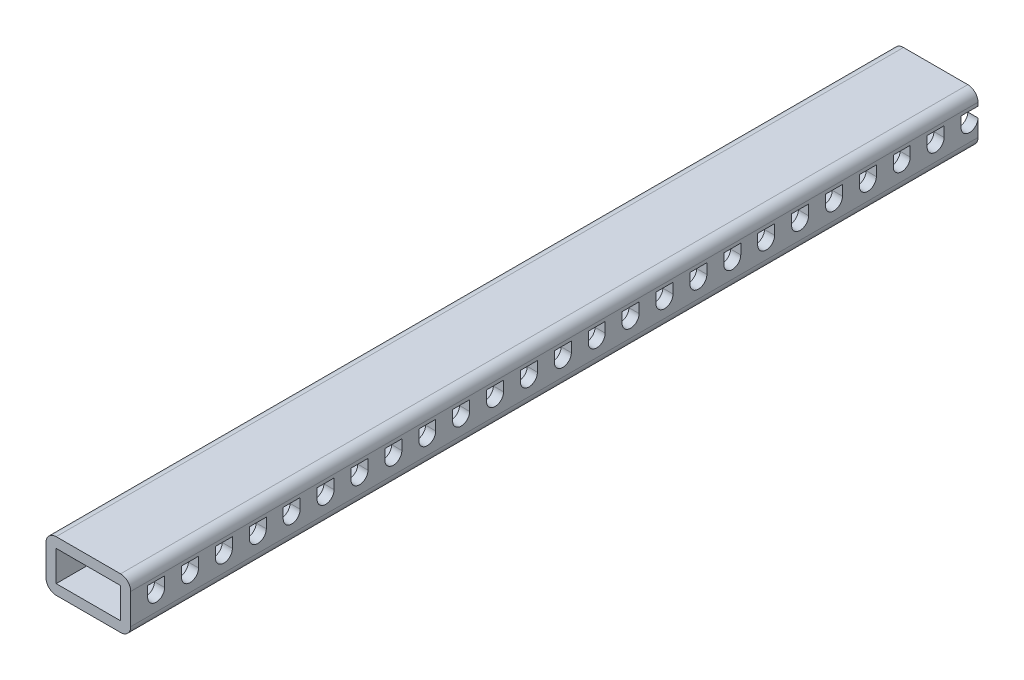
SolidWorks part; units mm, degrees
ref_plane "Front Plane" through (0, 0, 0) normal (0, 0, 1) x (1, 0, 0)
ref_plane "Top Plane" through (0, 0, 0) normal (0, 1, 0) x (1, 0, 0)
ref_plane "Right Plane" through (0, 0, 0) normal (1, 0, 0) x (0, 0, -1)
sketch "Sketch1" plane through (0, 0, 0) normal (0, 0, 1) x (1, 0, 0)
  line L1 (-12.5, 7.5) -> (12.5, 7.5)
  line L2 (-12.5, 7.5) -> (-12.5, -7.5)
  line L3 (-12.5, -7.5) -> (12.5, -7.5)
  line L4 (12.5, 7.5) -> (12.5, -7.5)
  line L5 (-12.5, 7.5) -> (12.5, -7.5) construction
  line L6 (-12.5, -7.5) -> (12.5, 7.5) construction
  point P0 (0, 0)
  dimension "D1" = 25
  dimension "D2" = 15
extrude "Boss-Extrude1" add sketch "Sketch1" along normal blind 520
sketch "Sketch2" plane through (0, 0, 520) normal (0, 0, 1) x (1, 0, 0)
  line L0 (-12.5, 7.5) -> (-12.5, -7.5) construction
  line L1 (-9.5, -4.5) -> (9.5, -4.5)
  line L2 (-9.5, -4.5) -> (-9.5, 4.5)
  line L3 (-9.5, 4.5) -> (9.5, 4.5)
  line L4 (9.5, -4.5) -> (9.5, 4.5)
  line L5 (-9.5, -4.5) -> (9.5, 4.5) construction
  line L6 (-9.5, 4.5) -> (9.5, -4.5) construction
  line L7 (12.5, 7.5) -> (-12.5, 7.5) construction
  point P0 (0, 0)
  dimension "D1" = 3
  dimension "D2" = 3
extrude "Cut-Extrude1" cut sketch "Sketch2" against normal blind 263
sketch "Sketch3" plane through (12.5, 0, 0) normal (1, 0, 0) x (0, 0, -1)
  line L1 (-520, 7.5) -> (0, 7.5) construction
  line L2 (-515, 3.5) -> (-510, 3.5)
  line L3 (-515, 3.5) -> (-515, 0.5)
  line L5 (-510, 3.5) -> (-510, 0.5)
  line L6 (-520, -7.5) -> (-520, 7.5) construction
  line L7 (-507.5, 7.5) -> (-507.5, 3.8883) construction
  line L8 (-505, 3.5) -> (-505, 0.5)
  line L9 (-500, 3.5) -> (-500, 0.5)
  line L10 (-500, 3.5) -> (-505, 3.5)
  line L11 (-497.5, 7.5) -> (-497.5, 3.8883) construction
  line L12 (-487.5, 7.5) -> (-487.5, 3.8883) construction
  line L13 (-495, 3.5) -> (-490, 3.5)
  line L14 (-495, 3.5) -> (-495, 0.5)
  line L15 (-490, 3.5) -> (-490, 0.5)
  line L16 (-485, 3.5) -> (-485, 0.5)
  line L17 (-480, 3.5) -> (-480, 0.5)
  line L18 (-480, 3.5) -> (-485, 3.5)
  line L19 (-477.5, 7.5) -> (-477.5, 3.8883) construction
  line L20 (-467.5, 7.5) -> (-467.5, 3.8883) construction
  line L21 (-485, 3.5) -> (-485, 0.5)
  line L22 (-480, 3.5) -> (-480, 0.5)
  line L23 (-480, 3.5) -> (-485, 3.5)
  line L24 (-475, 3.5) -> (-470, 3.5)
  line L25 (-475, 3.5) -> (-475, 0.5)
  line L26 (-470, 3.5) -> (-470, 0.5)
  line L27 (-465, 3.5) -> (-465, 0.5)
  line L28 (-460, 3.5) -> (-460, 0.5)
  line L29 (-460, 3.5) -> (-465, 3.5)
  line L30 (-457.5, 7.5) -> (-457.5, 3.8883) construction
  line L31 (-447.5, 7.5) -> (-447.5, 3.8883) construction
  line L32 (-437.5, 7.5) -> (-437.5, 3.8883) construction
  line L33 (-427.5, 7.5) -> (-427.5, 3.8883) construction
  line L34 (-465, 3.5) -> (-465, 0.5)
  line L35 (-460, 3.5) -> (-460, 0.5)
  line L36 (-460, 3.5) -> (-465, 3.5)
  line L37 (-455, 3.5) -> (-450, 3.5)
  line L38 (-455, 3.5) -> (-455, 0.5)
  line L39 (-450, 3.5) -> (-450, 0.5)
  line L40 (-455, 3.5) -> (-450, 3.5)
  line L41 (-455, 3.5) -> (-455, 0.5)
  line L42 (-450, 3.5) -> (-450, 0.5)
  line L43 (-445, 3.5) -> (-445, 0.5)
  line L44 (-440, 3.5) -> (-440, 0.5)
  line L45 (-440, 3.5) -> (-445, 3.5)
  line L46 (-435, 3.5) -> (-430, 3.5)
  line L47 (-435, 3.5) -> (-435, 0.5)
  line L48 (-430, 3.5) -> (-430, 0.5)
  line L49 (-425, 3.5) -> (-425, 0.5)
  line L50 (-420, 3.5) -> (-420, 0.5)
  line L51 (-420, 3.5) -> (-425, 3.5)
  line L52 (-417.5, 7.5) -> (-417.5, 3.8883) construction
  line L53 (-407.5, 7.5) -> (-407.5, 3.8883) construction
  line L54 (-397.5, 7.5) -> (-397.5, 3.8883) construction
  line L55 (-387.5, 7.5) -> (-387.5, 3.8883) construction
  line L56 (-377.5, 7.5) -> (-377.5, 3.8883) construction
  line L57 (-367.5, 7.5) -> (-367.5, 3.8883) construction
  line L58 (-357.5, 7.5) -> (-357.5, 3.8883) construction
  line L59 (-347.5, 7.5) -> (-347.5, 3.8883) construction
  line L60 (-425, 3.5) -> (-425, 0.5)
  line L61 (-420, 3.5) -> (-420, 0.5)
  line L62 (-420, 3.5) -> (-425, 3.5)
  line L63 (-415, 3.5) -> (-410, 3.5)
  line L64 (-415, 3.5) -> (-415, 0.5)
  line L65 (-410, 3.5) -> (-410, 0.5)
  line L66 (-405, 3.5) -> (-405, 0.5)
  line L67 (-400, 3.5) -> (-400, 0.5)
  line L68 (-400, 3.5) -> (-405, 3.5)
  line L69 (-405, 3.5) -> (-405, 0.5)
  line L70 (-400, 3.5) -> (-400, 0.5)
  line L71 (-400, 3.5) -> (-405, 3.5)
  line L72 (-395, 3.5) -> (-390, 3.5)
  line L73 (-395, 3.5) -> (-395, 0.5)
  line L74 (-390, 3.5) -> (-390, 0.5)
  line L75 (-395, 3.5) -> (-390, 3.5)
  line L76 (-395, 3.5) -> (-395, 0.5)
  line L77 (-390, 3.5) -> (-390, 0.5)
  line L78 (-385, 3.5) -> (-385, 0.5)
  line L79 (-380, 3.5) -> (-380, 0.5)
  line L80 (-380, 3.5) -> (-385, 3.5)
  line L81 (-375, 3.5) -> (-370, 3.5)
  line L82 (-375, 3.5) -> (-375, 0.5)
  line L83 (-370, 3.5) -> (-370, 0.5)
  line L84 (-375, 3.5) -> (-370, 3.5)
  line L85 (-375, 3.5) -> (-375, 0.5)
  line L86 (-370, 3.5) -> (-370, 0.5)
  line L87 (-365, 3.5) -> (-365, 0.5)
  line L88 (-360, 3.5) -> (-360, 0.5)
  line L89 (-360, 3.5) -> (-365, 3.5)
  line L90 (-355, 3.5) -> (-350, 3.5)
  line L91 (-355, 3.5) -> (-355, 0.5)
  line L92 (-350, 3.5) -> (-350, 0.5)
  line L93 (-345, 3.5) -> (-345, 0.5)
  line L94 (-340, 3.5) -> (-340, 0.5)
  line L95 (-340, 3.5) -> (-345, 3.5)
  line L96 (-345, 3.5) -> (-345, 0.5)
  line L97 (-315, 3.5) -> (-310, 3.5)
  line L98 (-315, 3.5) -> (-315, 0.5)
  line L99 (-310, 3.5) -> (-310, 0.5)
  line L100 (-337.5, 7.5) -> (-337.5, 3.8883) construction
  line L101 (-327.5, 7.5) -> (-327.5, 3.8883) construction
  line L102 (-317.5, 7.5) -> (-317.5, 3.8883) construction
  line L103 (-340, 3.5) -> (-340, 0.5)
  line L104 (-340, 3.5) -> (-345, 3.5)
  line L105 (-335, 3.5) -> (-330, 3.5)
  line L106 (-335, 3.5) -> (-335, 0.5)
  line L107 (-330, 3.5) -> (-330, 0.5)
  line L108 (-325, 3.5) -> (-325, 0.5)
  line L109 (-320, 3.5) -> (-320, 0.5)
  line L110 (-320, 3.5) -> (-325, 3.5)
  line L111 (-325, 3.5) -> (-325, 0.5)
  line L112 (-320, 3.5) -> (-320, 0.5)
  line L113 (-320, 3.5) -> (-325, 3.5)
  line L114 (-307.5, 7.5) -> (-307.5, 3.8883) construction
  line L115 (-315, 3.5) -> (-310, 3.5)
  line L116 (-315, 3.5) -> (-315, 0.5)
  line L117 (-310, 3.5) -> (-310, 0.5)
  line L118 (-315, 3.5) -> (-310, 3.5)
  line L119 (-315, 3.5) -> (-315, 0.5)
  line L120 (-310, 3.5) -> (-310, 0.5)
  line L121 (-305, 3.5) -> (-305, 0.5)
  line L122 (-300, 3.5) -> (-300, 0.5)
  line L123 (-300, 3.5) -> (-305, 3.5)
  arc A0 (-515, 0.5) -> (-510, 0.5) centre (-512.5, 0.5) ccw
  arc A1 (-500, 0.5) -> (-505, 0.5) centre (-502.5, 0.5) cw
  arc A2 (-495, 0.5) -> (-490, 0.5) centre (-492.5, 0.5) ccw
  arc A3 (-480, 0.5) -> (-485, 0.5) centre (-482.5, 0.5) cw
  arc A4 (-480, 0.5) -> (-485, 0.5) centre (-482.5, 0.5) cw
  arc A5 (-475, 0.5) -> (-470, 0.5) centre (-472.5, 0.5) ccw
  arc A6 (-460, 0.5) -> (-465, 0.5) centre (-462.5, 0.5) cw
  arc A7 (-460, 0.5) -> (-465, 0.5) centre (-462.5, 0.5) cw
  arc A8 (-455, 0.5) -> (-450, 0.5) centre (-452.5, 0.5) ccw
  arc A9 (-455, 0.5) -> (-450, 0.5) centre (-452.5, 0.5) ccw
  arc A10 (-440, 0.5) -> (-445, 0.5) centre (-442.5, 0.5) cw
  arc A11 (-435, 0.5) -> (-430, 0.5) centre (-432.5, 0.5) ccw
  arc A12 (-420, 0.5) -> (-425, 0.5) centre (-422.5, 0.5) cw
  arc A13 (-420, 0.5) -> (-425, 0.5) centre (-422.5, 0.5) cw
  arc A14 (-415, 0.5) -> (-410, 0.5) centre (-412.5, 0.5) ccw
  arc A15 (-400, 0.5) -> (-405, 0.5) centre (-402.5, 0.5) cw
  arc A16 (-400, 0.5) -> (-405, 0.5) centre (-402.5, 0.5) cw
  arc A17 (-395, 0.5) -> (-390, 0.5) centre (-392.5, 0.5) ccw
  arc A18 (-395, 0.5) -> (-390, 0.5) centre (-392.5, 0.5) ccw
  arc A19 (-380, 0.5) -> (-385, 0.5) centre (-382.5, 0.5) cw
  arc A20 (-375, 0.5) -> (-370, 0.5) centre (-372.5, 0.5) ccw
  arc A21 (-375, 0.5) -> (-370, 0.5) centre (-372.5, 0.5) ccw
  arc A22 (-360, 0.5) -> (-365, 0.5) centre (-362.5, 0.5) cw
  arc A23 (-355, 0.5) -> (-350, 0.5) centre (-352.5, 0.5) ccw
  arc A24 (-340, 0.5) -> (-345, 0.5) centre (-342.5, 0.5) cw
  arc A25 (-315, 0.5) -> (-310, 0.5) centre (-312.5, 0.5) ccw
  arc A26 (-340, 0.5) -> (-345, 0.5) centre (-342.5, 0.5) cw
  arc A27 (-335, 0.5) -> (-330, 0.5) centre (-332.5, 0.5) ccw
  arc A28 (-320, 0.5) -> (-325, 0.5) centre (-322.5, 0.5) cw
  arc A29 (-320, 0.5) -> (-325, 0.5) centre (-322.5, 0.5) cw
  arc A30 (-315, 0.5) -> (-310, 0.5) centre (-312.5, 0.5) ccw
  arc A31 (-315, 0.5) -> (-310, 0.5) centre (-312.5, 0.5) ccw
  arc A32 (-300, 0.5) -> (-305, 0.5) centre (-302.5, 0.5) cw
  point P18 (-500, 2)
  dimension "D1" = 4
  dimension "D2" = 5
  dimension "D3" = 5
  dimension "D4" = 3
  dimension "D5" = 5
  dimension "D6" = 5
extrude "Cut-Extrude2" cut sketch "Sketch3" against normal blind 263 contours L3 A0 L5 L2 | A1 L9 L10 L8 | L14 A2 L15 L13 | A3 L17 L18 L16 | L25 A5 L26 L24 | A6 L28 L29 L27 | L38 A8 L39 L37 | A10 L44 L45 L43 | L47 A11 L48 L46 | A12 L50 L51 L49 | L64 A14 L65 L63 | A15 L67 L68 L66 | L73 A17 L74 L72 | A19 L79 L80 L78 | L82 A20 L83 L81 | A22 L88 L89 L87 | L91 A23 L92 L90 | A24 L94 L95 L93 | L106 A27 L107 L105 | A28 L109 L110 L108 | L98 A25 L99 L97 | A32 L122 L123 L121
fillet "Fillet1" radius 3 4 edges at (-12.5, -7.5, 260) (12.5, -7.5, 260) (12.5, 7.5, 260) (-12.5, 7.5, 260)
sketch "Sketch7" plane through (12.5, 0, 0) normal (1, 0, 0) x (0, 0, -1)
  line L0 (-297.5, 4.5) -> (-297.5, 1.6532) construction
  line L2 (-300, 0.5) -> (-300, 3.5)
  line L3 (-300, 3.5) -> (-305, 3.5)
  line L4 (-305, 0.5) -> (-305, 3.5)
  line L5 (-300, -2.5) -> (-305, 3.5) construction
  line L6 (-300, 3.5) -> (-305, -2.5) construction
  line L7 (0, 4.5) -> (-520, 4.5) construction
  line L8 (-295, 3.5) -> (-290, -2.5) construction
  line L9 (-295, -2.5) -> (-290, 3.5) construction
  line L10 (-290, 0.5) -> (-290, 3.5)
  line L11 (-295, 3.5) -> (-290, 3.5)
  line L12 (-295, 0.5) -> (-295, 3.5)
  line L13 (-287.5, 4.5) -> (-287.5, 0.5) construction
  line L14 (-280, -2.5) -> (-285, 3.5) construction
  line L15 (-280, 3.5) -> (-285, -2.5) construction
  line L16 (-275, 3.5) -> (-270, -2.5) construction
  line L17 (-275, -2.5) -> (-270, 3.5) construction
  line L18 (-277.5, 4.5) -> (-277.5, 1.6532) construction
  line L19 (-280, 0.5) -> (-280, 3.5)
  line L20 (-280, 3.5) -> (-285, 3.5)
  line L21 (-285, 0.5) -> (-285, 3.5)
  line L22 (-270, 0.5) -> (-270, 3.5)
  line L23 (-275, 3.5) -> (-270, 3.5)
  line L24 (-275, 0.5) -> (-275, 3.5)
  line L25 (-275, 3.5) -> (-270, -2.5) construction
  line L26 (-275, -2.5) -> (-270, 3.5) construction
  line L27 (-267.5, 4.5) -> (-267.5, 0.5) construction
  line L28 (-260, -2.5) -> (-265, 3.5) construction
  line L29 (-260, 3.5) -> (-265, -2.5) construction
  line L30 (-255, 3.5) -> (-250, -2.5) construction
  line L31 (-255, -2.5) -> (-250, 3.5) construction
  line L32 (-257.5, 4.5) -> (-257.5, 1.6532) construction
  line L33 (-270, 0.5) -> (-270, 3.5)
  line L34 (-275, 3.5) -> (-270, 3.5)
  line L35 (-275, 0.5) -> (-275, 3.5)
  line L36 (-260, 0.5) -> (-260, 3.5)
  line L37 (-260, 3.5) -> (-265, 3.5)
  line L38 (-265, 0.5) -> (-265, 3.5)
  line L39 (-250, 0.5) -> (-250, 3.5)
  line L40 (-255, 3.5) -> (-250, 3.5)
  line L41 (-255, 0.5) -> (-255, 3.5)
  line L42 (-255, 3.5) -> (-250, -2.5) construction
  line L43 (-255, -2.5) -> (-250, 3.5) construction
  line L44 (-247.5, 4.5) -> (-247.5, 0.5) construction
  line L45 (-240, -2.5) -> (-245, 3.5) construction
  line L46 (-240, 3.5) -> (-245, -2.5) construction
  line L47 (-237.5, 4.5) -> (-237.5, 1.6532) construction
  line L48 (-240, -2.5) -> (-245, 3.5) construction
  line L49 (-240, 3.5) -> (-245, -2.5) construction
  line L50 (-235, 3.5) -> (-230, -2.5) construction
  line L51 (-235, -2.5) -> (-230, 3.5) construction
  line L52 (-227.5, 4.5) -> (-227.5, 0.5) construction
  line L53 (-220, -2.5) -> (-225, 3.5) construction
  line L54 (-220, 3.5) -> (-225, -2.5) construction
  line L55 (-215, 3.5) -> (-210, -2.5) construction
  line L56 (-215, -2.5) -> (-210, 3.5) construction
  line L57 (-217.5, 4.5) -> (-217.5, 1.6532) construction
  line L58 (-250, 0.5) -> (-250, 3.5)
  line L59 (-255, 3.5) -> (-250, 3.5)
  line L60 (-255, 0.5) -> (-255, 3.5)
  line L61 (-240, 0.5) -> (-240, 3.5)
  line L62 (-240, 3.5) -> (-245, 3.5)
  line L63 (-245, 0.5) -> (-245, 3.5)
  line L64 (-240, 0.5) -> (-240, 3.5)
  line L65 (-240, 3.5) -> (-245, 3.5)
  line L66 (-245, 0.5) -> (-245, 3.5)
  line L67 (-230, 0.5) -> (-230, 3.5)
  line L68 (-235, 3.5) -> (-230, 3.5)
  line L69 (-235, 0.5) -> (-235, 3.5)
  line L70 (-220, 0.5) -> (-220, 3.5)
  line L71 (-220, 3.5) -> (-225, 3.5)
  line L72 (-225, 0.5) -> (-225, 3.5)
  line L73 (-210, 0.5) -> (-210, 3.5)
  line L74 (-215, 3.5) -> (-210, 3.5)
  line L75 (-215, 0.5) -> (-215, 3.5)
  line L76 (-215, 3.5) -> (-210, -2.5) construction
  line L77 (-215, -2.5) -> (-210, 3.5) construction
  line L78 (-207.5, 4.5) -> (-207.5, 0.5) construction
  line L79 (-200, -2.5) -> (-205, 3.5) construction
  line L80 (-200, 3.5) -> (-205, -2.5) construction
  line L81 (-195, 3.5) -> (-190, -2.5) construction
  line L82 (-195, -2.5) -> (-190, 3.5) construction
  line L83 (-197.5, 4.5) -> (-197.5, 1.6532) construction
  line L84 (-195, 3.5) -> (-190, -2.5) construction
  line L85 (-195, -2.5) -> (-190, 3.5) construction
  line L86 (-187.5, 4.5) -> (-187.5, 0.5) construction
  line L87 (-180, -2.5) -> (-185, 3.5) construction
  line L88 (-180, 3.5) -> (-185, -2.5) construction
  line L89 (-177.5, 4.5) -> (-177.5, 1.6532) construction
  line L90 (-180, -2.5) -> (-185, 3.5) construction
  line L91 (-180, 3.5) -> (-185, -2.5) construction
  line L92 (-175, 3.5) -> (-170, -2.5) construction
  line L93 (-175, -2.5) -> (-170, 3.5) construction
  line L94 (-167.5, 4.5) -> (-167.5, 0.5) construction
  line L95 (-160, -2.5) -> (-165, 3.5) construction
  line L96 (-160, 3.5) -> (-165, -2.5) construction
  line L97 (-157.5, 4.5) -> (-157.5, 1.6532) construction
  line L98 (-160, -2.5) -> (-165, 3.5) construction
  line L99 (-160, 3.5) -> (-165, -2.5) construction
  line L100 (-155, 3.5) -> (-150, -2.5) construction
  line L101 (-155, -2.5) -> (-150, 3.5) construction
  line L102 (-147.5, 4.5) -> (-147.5, 0.5) construction
  line L103 (-140, -2.5) -> (-145, 3.5) construction
  line L104 (-140, 3.5) -> (-145, -2.5) construction
  line L105 (-135, 3.5) -> (-130, -2.5) construction
  line L106 (-135, -2.5) -> (-130, 3.5) construction
  line L107 (-137.5, 4.5) -> (-137.5, 1.6532) construction
  line L108 (-210, 0.5) -> (-210, 3.5)
  line L109 (-215, 3.5) -> (-210, 3.5)
  line L110 (-215, 0.5) -> (-215, 3.5)
  line L111 (-200, 0.5) -> (-200, 3.5)
  line L112 (-200, 3.5) -> (-205, 3.5)
  line L113 (-205, 0.5) -> (-205, 3.5)
  line L114 (-190, 0.5) -> (-190, 3.5)
  line L115 (-195, 3.5) -> (-190, 3.5)
  line L116 (-195, 0.5) -> (-195, 3.5)
  line L117 (-190, 0.5) -> (-190, 3.5)
  line L118 (-195, 3.5) -> (-190, 3.5)
  line L119 (-195, 0.5) -> (-195, 3.5)
  line L120 (-180, 0.5) -> (-180, 3.5)
  line L121 (-180, 3.5) -> (-185, 3.5)
  line L122 (-185, 0.5) -> (-185, 3.5)
  line L123 (-180, 0.5) -> (-180, 3.5)
  line L124 (-180, 3.5) -> (-185, 3.5)
  line L125 (-185, 0.5) -> (-185, 3.5)
  line L126 (-170, 0.5) -> (-170, 3.5)
  line L127 (-175, 3.5) -> (-170, 3.5)
  line L128 (-175, 0.5) -> (-175, 3.5)
  line L129 (-160, 0.5) -> (-160, 3.5)
  line L130 (-160, 3.5) -> (-165, 3.5)
  line L131 (-165, 0.5) -> (-165, 3.5)
  line L132 (-160, 0.5) -> (-160, 3.5)
  line L133 (-160, 3.5) -> (-165, 3.5)
  line L134 (-165, 0.5) -> (-165, 3.5)
  line L135 (-150, 0.5) -> (-150, 3.5)
  line L136 (-155, 3.5) -> (-150, 3.5)
  line L137 (-155, 0.5) -> (-155, 3.5)
  line L138 (-140, 0.5) -> (-140, 3.5)
  line L139 (-140, 3.5) -> (-145, 3.5)
  line L140 (-145, 0.5) -> (-145, 3.5)
  line L141 (-130, 0.5) -> (-130, 3.5)
  line L142 (-135, 3.5) -> (-130, 3.5)
  line L143 (-135, 0.5) -> (-135, 3.5)
  line L144 (-135, 3.5) -> (-130, -2.5) construction
  line L145 (-135, -2.5) -> (-130, 3.5) construction
  line L146 (-127.5, 4.5) -> (-127.5, 0.5) construction
  line L147 (-120, -2.5) -> (-125, 3.5) construction
  line L148 (-120, 3.5) -> (-125, -2.5) construction
  line L149 (-115, 3.5) -> (-110, -2.5) construction
  line L150 (-115, -2.5) -> (-110, 3.5) construction
  line L151 (-117.5, 4.5) -> (-117.5, 1.6532) construction
  line L152 (-115, 3.5) -> (-110, -2.5) construction
  line L153 (-115, -2.5) -> (-110, 3.5) construction
  line L154 (-107.5, 4.5) -> (-107.5, 0.5) construction
  line L155 (-100, -2.5) -> (-105, 3.5) construction
  line L156 (-100, 3.5) -> (-105, -2.5) construction
  line L157 (-95, 3.5) -> (-90, -2.5) construction
  line L158 (-95, -2.5) -> (-90, 3.5) construction
  line L159 (-97.5, 4.5) -> (-97.5, 1.6532) construction
  line L160 (-95, 3.5) -> (-90, -2.5) construction
  line L161 (-95, -2.5) -> (-90, 3.5) construction
  line L162 (-87.5, 4.5) -> (-87.5, 0.5) construction
  line L163 (-80, -2.5) -> (-85, 3.5) construction
  line L164 (-80, 3.5) -> (-85, -2.5) construction
  line L165 (-77.5, 4.5) -> (-77.5, 1.6532) construction
  line L166 (-80, -2.5) -> (-85, 3.5) construction
  line L167 (-80, 3.5) -> (-85, -2.5) construction
  line L168 (-75, 3.5) -> (-70, -2.5) construction
  line L169 (-75, -2.5) -> (-70, 3.5) construction
  line L170 (-130, 0.5) -> (-130, 3.5)
  line L171 (-135, 3.5) -> (-130, 3.5)
  line L172 (-135, 0.5) -> (-135, 3.5)
  line L173 (-120, 0.5) -> (-120, 3.5)
  line L174 (-120, 3.5) -> (-125, 3.5)
  line L175 (-125, 0.5) -> (-125, 3.5)
  line L176 (-110, 0.5) -> (-110, 3.5)
  line L177 (-115, 3.5) -> (-110, 3.5)
  line L178 (-115, 0.5) -> (-115, 3.5)
  line L179 (-110, 0.5) -> (-110, 3.5)
  line L180 (-115, 3.5) -> (-110, 3.5)
  line L181 (-115, 0.5) -> (-115, 3.5)
  line L182 (-100, 0.5) -> (-100, 3.5)
  line L183 (-100, 3.5) -> (-105, 3.5)
  line L184 (-105, 0.5) -> (-105, 3.5)
  line L185 (-90, 0.5) -> (-90, 3.5)
  line L186 (-95, 3.5) -> (-90, 3.5)
  line L187 (-95, 0.5) -> (-95, 3.5)
  line L188 (-90, 0.5) -> (-90, 3.5)
  line L189 (-95, 3.5) -> (-90, 3.5)
  line L190 (-95, 0.5) -> (-95, 3.5)
  line L191 (-80, 0.5) -> (-80, 3.5)
  line L192 (-80, 3.5) -> (-85, 3.5)
  line L193 (-85, 0.5) -> (-85, 3.5)
  line L194 (-80, 0.5) -> (-80, 3.5)
  line L195 (-80, 3.5) -> (-85, 3.5)
  line L196 (-85, 0.5) -> (-85, 3.5)
  line L197 (-70, 0.5) -> (-70, 3.5)
  line L198 (-75, 3.5) -> (-70, 3.5)
  line L199 (-75, 0.5) -> (-75, 3.5)
  line L200 (-75, 3.5) -> (-70, -2.5) construction
  line L201 (-75, -2.5) -> (-70, 3.5) construction
  line L202 (-75, 3.5) -> (-70, -2.5) construction
  line L203 (-75, -2.5) -> (-70, 3.5) construction
  line L204 (-67.5, 4.5) -> (-67.5, 0.5) construction
  line L205 (-60, -2.5) -> (-65, 3.5) construction
  line L206 (-60, 3.5) -> (-65, -2.5) construction
  line L207 (-57.5, 4.5) -> (-57.5, 1.6532) construction
  line L208 (-60, -2.5) -> (-65, 3.5) construction
  line L209 (-60, 3.5) -> (-65, -2.5) construction
  line L210 (-55, 3.5) -> (-50, -2.5) construction
  line L211 (-55, -2.5) -> (-50, 3.5) construction
  line L212 (-47.5, 4.5) -> (-47.5, 0.5) construction
  line L213 (-40, -2.5) -> (-45, 3.5) construction
  line L214 (-40, 3.5) -> (-45, -2.5) construction
  line L215 (-37.5, 4.5) -> (-37.5, 1.6532) construction
  line L216 (-40, -2.5) -> (-45, 3.5) construction
  line L217 (-40, 3.5) -> (-45, -2.5) construction
  line L218 (-35, 3.5) -> (-30, -2.5) construction
  line L219 (-35, -2.5) -> (-30, 3.5) construction
  line L220 (-27.5, 4.5) -> (-27.5, 0.5) construction
  line L221 (-20, -2.5) -> (-25, 3.5) construction
  line L222 (-20, 3.5) -> (-25, -2.5) construction
  line L223 (-17.5, 4.5) -> (-17.5, 1.6532) construction
  line L224 (-20, -2.5) -> (-25, 3.5) construction
  line L225 (-20, 3.5) -> (-25, -2.5) construction
  line L226 (-70, 0.5) -> (-70, 3.5)
  line L227 (-75, 3.5) -> (-70, 3.5)
  line L228 (-75, 0.5) -> (-75, 3.5)
  line L229 (-70, 0.5) -> (-70, 3.5)
  line L230 (-75, 3.5) -> (-70, 3.5)
  line L231 (-75, 0.5) -> (-75, 3.5)
  line L232 (-60, 0.5) -> (-60, 3.5)
  line L233 (-60, 3.5) -> (-65, 3.5)
  line L234 (-65, 0.5) -> (-65, 3.5)
  line L235 (-60, 0.5) -> (-60, 3.5)
  line L236 (-60, 3.5) -> (-65, 3.5)
  line L237 (-65, 0.5) -> (-65, 3.5)
  line L238 (-50, 0.5) -> (-50, 3.5)
  line L239 (-55, 3.5) -> (-50, 3.5)
  line L240 (-55, 0.5) -> (-55, 3.5)
  line L241 (-40, 0.5) -> (-40, 3.5)
  line L242 (-40, 3.5) -> (-45, 3.5)
  line L243 (-45, 0.5) -> (-45, 3.5)
  line L244 (-40, 0.5) -> (-40, 3.5)
  line L245 (-40, 3.5) -> (-45, 3.5)
  line L246 (-45, 0.5) -> (-45, 3.5)
  line L247 (-30, 0.5) -> (-30, 3.5)
  line L248 (-35, 3.5) -> (-30, 3.5)
  line L249 (-35, 0.5) -> (-35, 3.5)
  line L250 (-20, 0.5) -> (-20, 3.5)
  line L251 (-20, 3.5) -> (-25, 3.5)
  line L252 (-25, 0.5) -> (-25, 3.5)
  line L253 (-20, 0.5) -> (-20, 3.5)
  line L254 (-20, 3.5) -> (-25, 3.5)
  line L255 (-25, 0.5) -> (-25, 3.5)
  line L256 (-15, 3.5) -> (-10, -2.5) construction
  line L257 (-15, -2.5) -> (-10, 3.5) construction
  line L258 (-15, 3.5) -> (-10, -2.5) construction
  line L259 (-15, -2.5) -> (-10, 3.5) construction
  line L260 (-10, 0.5) -> (-10, 3.5)
  line L261 (-15, 3.5) -> (-10, 3.5)
  line L262 (-15, 0.5) -> (-15, 3.5)
  line L263 (-10, 0.5) -> (-10, 3.5)
  line L264 (-15, 3.5) -> (-10, 3.5)
  line L265 (-15, 0.5) -> (-15, 3.5)
  arc A0 (-305, 0.5) -> (-300, 0.5) centre (-302.5, 0.5) ccw
  arc A1 (-290, 0.5) -> (-295, 0.5) centre (-292.5, 0.5) cw
  arc A2 (-285, 0.5) -> (-280, 0.5) centre (-282.5, 0.5) ccw
  arc A3 (-270, 0.5) -> (-275, 0.5) centre (-272.5, 0.5) cw
  arc A4 (-270, 0.5) -> (-275, 0.5) centre (-272.5, 0.5) cw
  arc A5 (-265, 0.5) -> (-260, 0.5) centre (-262.5, 0.5) ccw
  arc A6 (-250, 0.5) -> (-255, 0.5) centre (-252.5, 0.5) cw
  arc A7 (-250, 0.5) -> (-255, 0.5) centre (-252.5, 0.5) cw
  arc A8 (-245, 0.5) -> (-240, 0.5) centre (-242.5, 0.5) ccw
  arc A9 (-245, 0.5) -> (-240, 0.5) centre (-242.5, 0.5) ccw
  arc A10 (-230, 0.5) -> (-235, 0.5) centre (-232.5, 0.5) cw
  arc A11 (-225, 0.5) -> (-220, 0.5) centre (-222.5, 0.5) ccw
  arc A12 (-210, 0.5) -> (-215, 0.5) centre (-212.5, 0.5) cw
  arc A13 (-210, 0.5) -> (-215, 0.5) centre (-212.5, 0.5) cw
  arc A14 (-205, 0.5) -> (-200, 0.5) centre (-202.5, 0.5) ccw
  arc A15 (-190, 0.5) -> (-195, 0.5) centre (-192.5, 0.5) cw
  arc A16 (-190, 0.5) -> (-195, 0.5) centre (-192.5, 0.5) cw
  arc A17 (-185, 0.5) -> (-180, 0.5) centre (-182.5, 0.5) ccw
  arc A18 (-185, 0.5) -> (-180, 0.5) centre (-182.5, 0.5) ccw
  arc A19 (-170, 0.5) -> (-175, 0.5) centre (-172.5, 0.5) cw
  arc A20 (-165, 0.5) -> (-160, 0.5) centre (-162.5, 0.5) ccw
  arc A21 (-165, 0.5) -> (-160, 0.5) centre (-162.5, 0.5) ccw
  arc A22 (-150, 0.5) -> (-155, 0.5) centre (-152.5, 0.5) cw
  arc A23 (-145, 0.5) -> (-140, 0.5) centre (-142.5, 0.5) ccw
  arc A24 (-130, 0.5) -> (-135, 0.5) centre (-132.5, 0.5) cw
  arc A25 (-130, 0.5) -> (-135, 0.5) centre (-132.5, 0.5) cw
  arc A26 (-125, 0.5) -> (-120, 0.5) centre (-122.5, 0.5) ccw
  arc A27 (-110, 0.5) -> (-115, 0.5) centre (-112.5, 0.5) cw
  arc A28 (-110, 0.5) -> (-115, 0.5) centre (-112.5, 0.5) cw
  arc A29 (-105, 0.5) -> (-100, 0.5) centre (-102.5, 0.5) ccw
  arc A30 (-90, 0.5) -> (-95, 0.5) centre (-92.5, 0.5) cw
  arc A31 (-90, 0.5) -> (-95, 0.5) centre (-92.5, 0.5) cw
  arc A32 (-85, 0.5) -> (-80, 0.5) centre (-82.5, 0.5) ccw
  arc A33 (-85, 0.5) -> (-80, 0.5) centre (-82.5, 0.5) ccw
  arc A34 (-70, 0.5) -> (-75, 0.5) centre (-72.5, 0.5) cw
  arc A35 (-70, 0.5) -> (-75, 0.5) centre (-72.5, 0.5) cw
  arc A36 (-70, 0.5) -> (-75, 0.5) centre (-72.5, 0.5) cw
  arc A37 (-65, 0.5) -> (-60, 0.5) centre (-62.5, 0.5) ccw
  arc A38 (-65, 0.5) -> (-60, 0.5) centre (-62.5, 0.5) ccw
  arc A39 (-50, 0.5) -> (-55, 0.5) centre (-52.5, 0.5) cw
  arc A40 (-45, 0.5) -> (-40, 0.5) centre (-42.5, 0.5) ccw
  arc A41 (-45, 0.5) -> (-40, 0.5) centre (-42.5, 0.5) ccw
  arc A42 (-30, 0.5) -> (-35, 0.5) centre (-32.5, 0.5) cw
  arc A43 (-25, 0.5) -> (-20, 0.5) centre (-22.5, 0.5) ccw
  arc A44 (-25, 0.5) -> (-20, 0.5) centre (-22.5, 0.5) ccw
  arc A45 (-10, 0.5) -> (-15, 0.5) centre (-12.5, 0.5) cw
  arc A46 (-10, 0.5) -> (-15, 0.5) centre (-12.5, 0.5) cw
  dimension "D1" = 5
  dimension "D2" = 5
  dimension "D3" = 5
extrude "Cut-Extrude6" cut sketch "Sketch7" against normal blind 29 contours A1 L10 L11 L12 | L21 A2 L19 L20 | A3 L22 L23 L24 | L38 A5 L36 L37 | A6 L39 L40 L41 | L63 A8 L61 L62 | A10 L67 L68 L69 | L72 A11 L70 L71 | A12 L73 L74 L75 | L113 A14 L111 L112 | A15 L114 L115 L116 | L122 A17 L120 L121 | A19 L126 L127 L128 | L131 A20 L129 L130 | A22 L135 L136 L137 | L140 A23 L138 L139 | A24 L141 L142 L143 | L175 A26 L173 L174 | A27 L176 L177 L178 | L184 A29 L182 L183 | A30 L185 L186 L187 | L193 A32 L191 L192 | A34 L197 L198 L199 | L234 A37 L232 L233 | A39 L238 L239 L240 | L243 A40 L241 L242 | A42 L247 L248 L249 | L252 A43 L250 L251 | A45 L260 L261 L262
sketch "Sketch8" plane through (0, 0, 0) normal (0, 0, -1) x (-1, 0, 0)
  line L0 (-9.5, 7.5) -> (9.5, 7.5) construction
  line L1 (9.5, -4.5) -> (-9.5, -4.5)
  line L2 (9.5, -4.5) -> (9.5, 4.5)
  line L3 (9.5, 4.5) -> (-9.5, 4.5)
  line L4 (-9.5, -4.5) -> (-9.5, 4.5)
  line L5 (9.5, -4.5) -> (-9.5, 4.5) construction
  line L6 (9.5, 4.5) -> (-9.5, -4.5) construction
  line L7 (-12.5, -4.5) -> (-12.5, 4.5) construction
  point P0 (0, 0)
  dimension "D1" = 3
  dimension "D2" = 3
extrude "Cut-Extrude7" cut sketch "Sketch8" against normal blind 535
sketch "Sketch9" plane through (-12.5, 0, 0) normal (-1, 0, 0) x (0, 0, 1)
  line L0 (0, 4.5) -> (0, -4.5) construction
  line L1 (300, 88.4828) -> (598.6461, 88.4828)
  line L2 (300, 88.4828) -> (300, -20.6862)
  line L3 (300, -20.6862) -> (598.6461, -20.6862)
  line L4 (598.6461, 88.4828) -> (598.6461, -20.6862)
  line L5 (300, 88.4828) -> (598.6461, -20.6862) construction
  line L6 (300, -20.6862) -> (598.6461, 88.4828) construction
  point P0 (449.3231, 33.8983)
  dimension "D1" = 300
extrude "Cut-Extrude8" cut sketch "Sketch9" against normal blind 64
sketch "Sketch10" plane through (0, 7.5, 0) normal (0, 1, 0) x (1, 0, 0)
  line L1 (-12.5, 0) -> (78.9417, 0)
  line L2 (-12.5, 0) -> (-12.5, -50)
  line L3 (-12.5, -50) -> (78.9417, -50)
  line L4 (78.9417, 0) -> (78.9417, -50)
  dimension "D1" = 50
extrude "Cut-Extrude9" cut sketch "Sketch10" against normal blind 70
